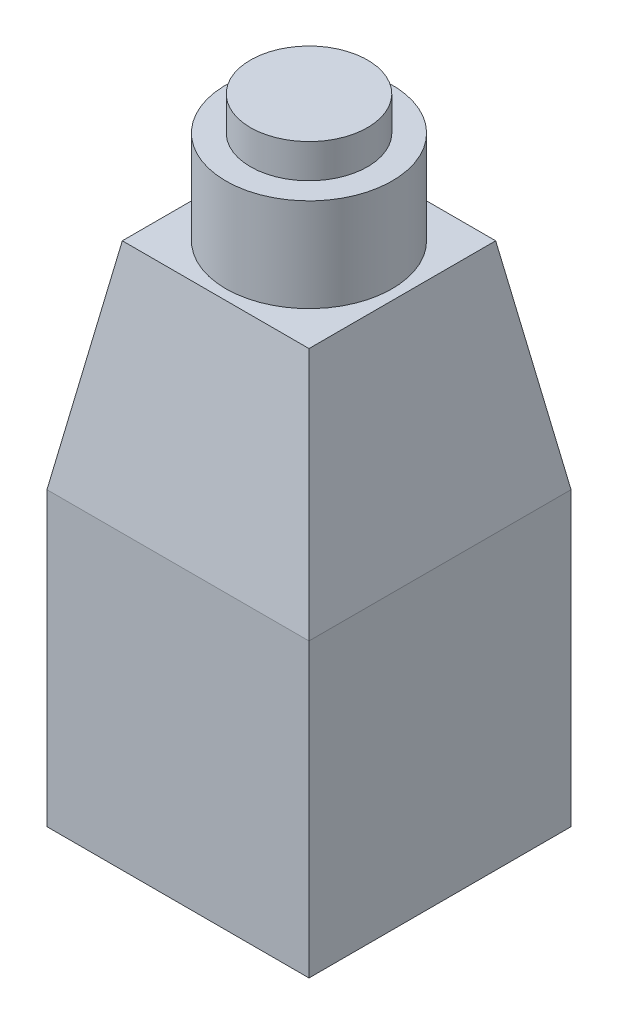
SolidWorks part; units mm, degrees
ref_plane "Спереди" through (0, 0, 0) normal (0, 0, 1) x (1, 0, 0)
ref_plane "Сверху" through (0, 0, 0) normal (0, 1, 0) x (1, 0, 0)
ref_plane "Справа" through (0, 0, 0) normal (1, 0, 0) x (0, 0, -1)
sketch "Эскиз1" plane through (0, 0, 0) normal (0, 1, 0) x (1, 0, 0)
  line L1 (-7.72, 7.72) -> (7.72, 7.72)
  line L2 (-7.72, 7.72) -> (-7.72, -7.72)
  line L3 (-7.72, -7.72) -> (7.72, -7.72)
  line L4 (7.72, 7.72) -> (7.72, -7.72)
  point P4 (-7.72, 0)
  point P5 (0, -7.72)
  dimension "D1" = 15.44
  dimension "D2" = 15.44
extrude "Бобышка-Вытянуть1" add sketch "Эскиз1" along normal blind 17.2
ref_plane "Плоскость1" through (0, 29.9, 0) normal (0, 1, 0) x (1, 0, 0)
sketch "Эскиз2" plane through (0, 29.9, 0) normal (0, 1, 0) x (1, 0, 0)
  line L1 (-5.5, 5.5) -> (5.5, 5.5)
  line L2 (-5.5, 5.5) -> (-5.5, -5.5)
  line L3 (-5.5, -5.5) -> (5.5, -5.5)
  line L4 (5.5, 5.5) -> (5.5, -5.5)
  line L5 (-5.5, 5.5) -> (5.5, -5.5) construction
  line L6 (-5.5, -5.5) -> (5.5, 5.5) construction
  point P0 (0, 0)
  dimension "D1" = 11
loft "По сечениям1" add profiles "Эскиз2" section "Эскиз2" section face at (0, 17.2, 0)
sketch "Эскиз3" plane through (0, 29.9, 0) normal (0, 1, 0) x (1, 0, 0)
  circle A0 centre (0, 0) radius 4.9
  dimension "D1" = 9.8
extrude "Бобышка-Вытянуть2" add sketch "Эскиз3" along normal blind 5.5
sketch "Эскиз4" plane through (0, 35.4, 0) normal (0, 1, 0) x (1, 0, 0)
  circle A0 centre (0, 0) radius 3.45
  dimension "D1" = 6.9
extrude "Бобышка-Вытянуть3" add sketch "Эскиз4" along normal blind 2
